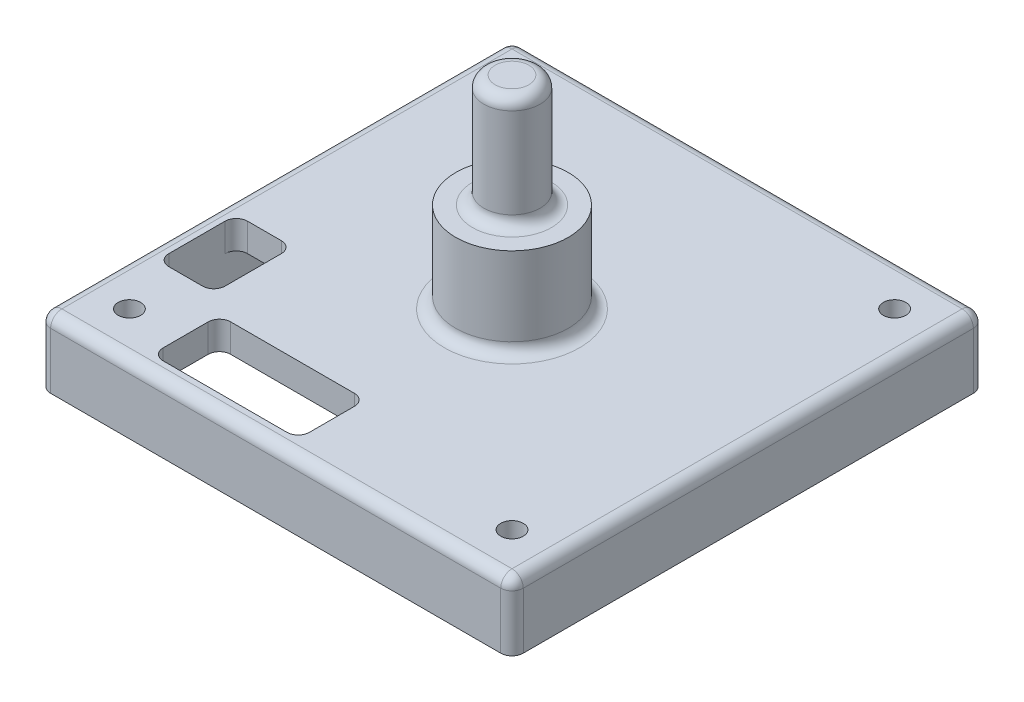
SolidWorks part; units mm, degrees
ref_plane "Front" through (0, 0, 0) normal (0, 0, 1) x (1, 0, 0)
ref_plane "Top" through (0, 0, 0) normal (0, 1, 0) x (1, 0, 0)
ref_plane "Right" through (0, 0, 0) normal (1, 0, 0) x (0, 0, -1)
sketch "Sketch1" plane through (0, 0, 0) normal (0, 1, 0) x (1, 0, 0)
  line L1 (-21, 21) -> (21, 21)
  line L2 (-21, 21) -> (-21, -21)
  line L3 (-21, -21) -> (21, -21)
  line L4 (21, 21) -> (21, -21)
  line L5 (-21, 21) -> (21, -21) construction
  line L6 (-21, -21) -> (21, 21) construction
  point P0 (0, 0)
  dimension "D1" = 42
extrude "Boss-Extrude1" add sketch "Sketch1" along normal blind 6
sketch "Sketch2" plane through (0, 0, 0) normal (0, -1, 0) x (1, 0, 0)
  line L1 (-19.5, 19.5) -> (19.5, 19.5)
  line L2 (-19.5, 19.5) -> (-19.5, -19.5)
  line L3 (-19.5, -19.5) -> (19.5, -19.5)
  line L4 (19.5, 19.5) -> (19.5, -19.5)
  line L5 (-19.5, 19.5) -> (19.5, -19.5) construction
  line L6 (-19.5, -19.5) -> (19.5, 19.5) construction
  point P0 (0, 0)
  dimension "D1" = 39
extrude "Cut-Extrude1" cut sketch "Sketch2" against normal blind 3.5
sketch "Sketch3" plane through (0, 3.5, 0) normal (0, -1, 0) x (1, 0, 0)
  line L0 (19.5, 19.5) -> (-19.5, 19.5) construction
  line L1 (-19.5, 12) -> (-14.5, 12)
  line L2 (-19.5, 12) -> (-19.5, 5)
  line L3 (-19.5, 5) -> (-14.5, 5)
  line L4 (-14.5, 12) -> (-14.5, 5)
  line L5 (-19.5, 12) -> (-14.5, 5) construction
  line L6 (-19.5, 5) -> (-14.5, 12) construction
  line L7 (-12.5, 19.5) -> (0.5, 19.5)
  line L8 (-12.5, 19.5) -> (-12.5, 13.5)
  line L9 (-12.5, 13.5) -> (0.5, 13.5)
  line L10 (0.5, 19.5) -> (0.5, 13.5)
  line L11 (-12.5, 19.5) -> (0.5, 13.5) construction
  line L12 (-12.5, 13.5) -> (0.5, 19.5) construction
  line L13 (-19.5, 19.5) -> (-19.5, -19.5) construction
  line L14 (19.5, 19.5) -> (-19.5, 19.5) construction
  point P0 (-17, 8.5)
  point P5 (-6, 16.5)
  dimension "D1" = 7.5
  dimension "D2" = 7
  dimension "D3" = 5
  dimension "D4" = 6
  dimension "D5" = 7
  dimension "D6" = 13
extrude "Cut-Extrude2" cut sketch "Sketch3" against normal up to next
sketch "Sketch4" plane through (0, 3.5, 0) normal (0, -1, 0) x (1, 0, 0)
  line L0 (-19.5, 17) -> (-19.5, 19.5)
  line L1 (17, -17) -> (-17, -17) construction
  line L2 (17, -17) -> (17, 17) construction
  line L3 (17, 17) -> (-17, 17) construction
  line L4 (-17, -17) -> (-17, 17) construction
  line L5 (17, -17) -> (-17, 17) construction
  line L6 (17, 17) -> (-17, -17) construction
  line L7 (-19.5, 19.5) -> (-19.5, -19.5) construction
  line L8 (-19.5, 19.5) -> (-17, 19.5)
  line L9 (-12.5, 19.5) -> (-19.5, 19.5) construction
  line L10 (0, 35.0408) -> (0, -41.1433) construction
  line L11 (-36.6087, 0) -> (46.6213, 0) construction
  line L12 (19.5, 19.5) -> (17, 19.5)
  line L13 (19.5, 17) -> (19.5, 19.5)
  line L14 (-19.5, -19.5) -> (-17, -19.5)
  line L15 (-19.5, -17) -> (-19.5, -19.5)
  line L16 (19.5, -17) -> (19.5, -19.5)
  line L17 (19.5, -19.5) -> (17, -19.5)
  arc A0 (-19.5, 17) -> (-17, 19.5) centre (-17, 17) ccw
  arc A1 (19.5, 17) -> (17, 19.5) centre (17, 17) cw
  arc A2 (-19.5, -17) -> (-17, -19.5) centre (-17, -17) cw
  arc A3 (19.5, -17) -> (17, -19.5) centre (17, -17) ccw
  point P0 (0, 0)
  dimension "D1" = 34
  dimension "D2" = 5
extrude "Boss-Extrude2" add sketch "Sketch4" along normal blind 2
sketch "Sketch5" plane through (0, 1.5, 0) normal (0, -1, 0) x (1, 0, 0)
  circle A0 centre (-17, 17) radius 1
  circle A1 centre (17, 17) radius 1
  circle A2 centre (17, -17) radius 1
  circle A3 centre (-17, -17) radius 1
  dimension "D1" = 2
extrude "Cut-Extrude3" cut sketch "Sketch5" against normal through all
sketch "Sketch6" plane through (0, 6, 0) normal (0, 1, 0) x (1, 0, 0)
  circle A0 centre (0, 0) radius 5
  dimension "D1" = 10
extrude "Boss-Extrude3" add sketch "Sketch6" along normal blind 8
sketch "Sketch7" plane through (0, 14, 0) normal (0, 1, 0) x (1, 0, 0)
  circle A0 centre (0, 0) radius 2.5
  dimension "D1" = 5
extrude "Boss-Extrude4" add sketch "Sketch7" along normal blind 10
fillet "Fillet1" radius 1 19 edges at (0, 24, 2.5) (0, 6, -21) (-21, 6, 0) (0, 6, 21) (21, 6, 0) (-21, 3, 21) (-21, 3, -21) (21, 3, -21) (21, 3, 21) (-12.5, 4.75, 13.5) (-12.5, 4.75, 19.5) (0.5, 4.75, 19.5) (0.5, 4.75, 13.5) (-19.5, 4.75, 5) (-19.5, 4.75, 12) (-14.5, 4.75, 12) (-14.5, 4.75, 5) (0, 14, 2.5) (0, 6, 5)
